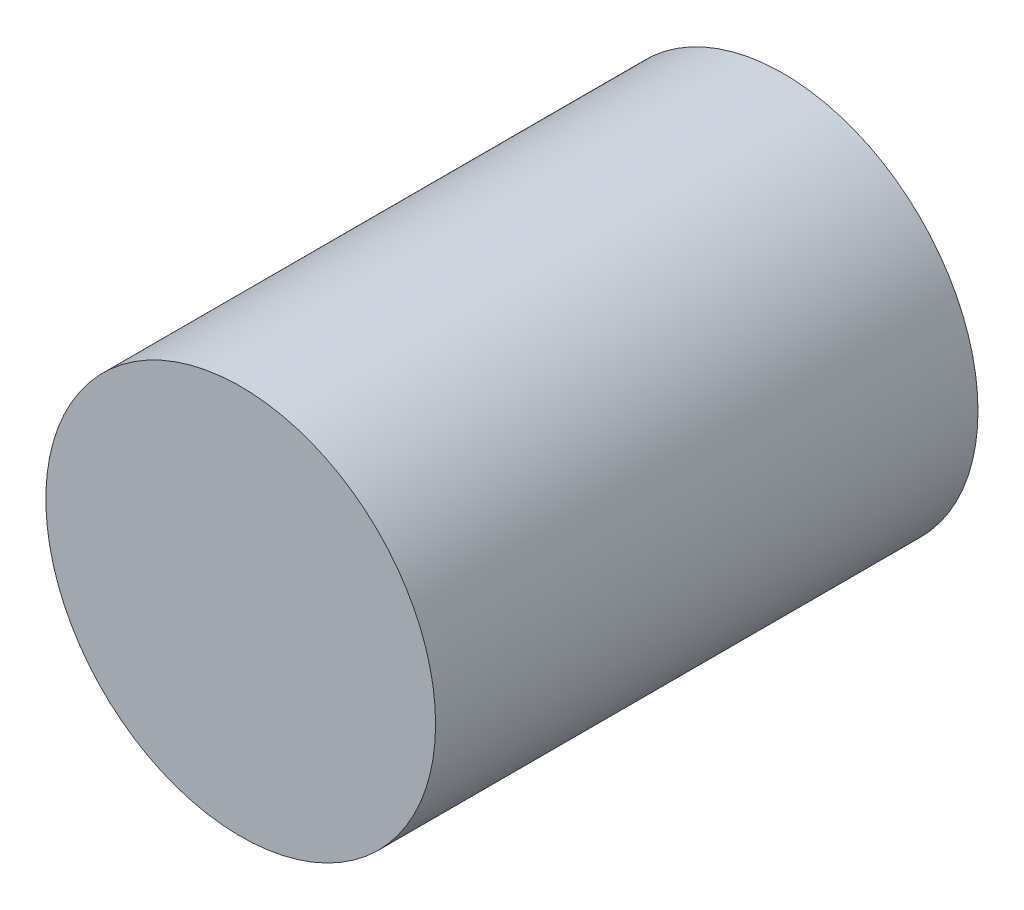
SolidWorks part; units mm, degrees
ref_plane "Front Plane" through (0, 0, 0) normal (0, 0, 1) x (1, 0, 0)
ref_plane "Top Plane" through (0, 0, 0) normal (0, 1, 0) x (1, 0, 0)
ref_plane "Right Plane" through (0, 0, 0) normal (1, 0, 0) x (0, 0, -1)
sketch "Sketch1" plane through (0, 0, 0) normal (0, 0, 1) x (1, 0, 0)
  circle A0 centre (0, 0) radius 3
extrude "Boss-Extrude1" add sketch "Sketch1" along normal blind 8.35
